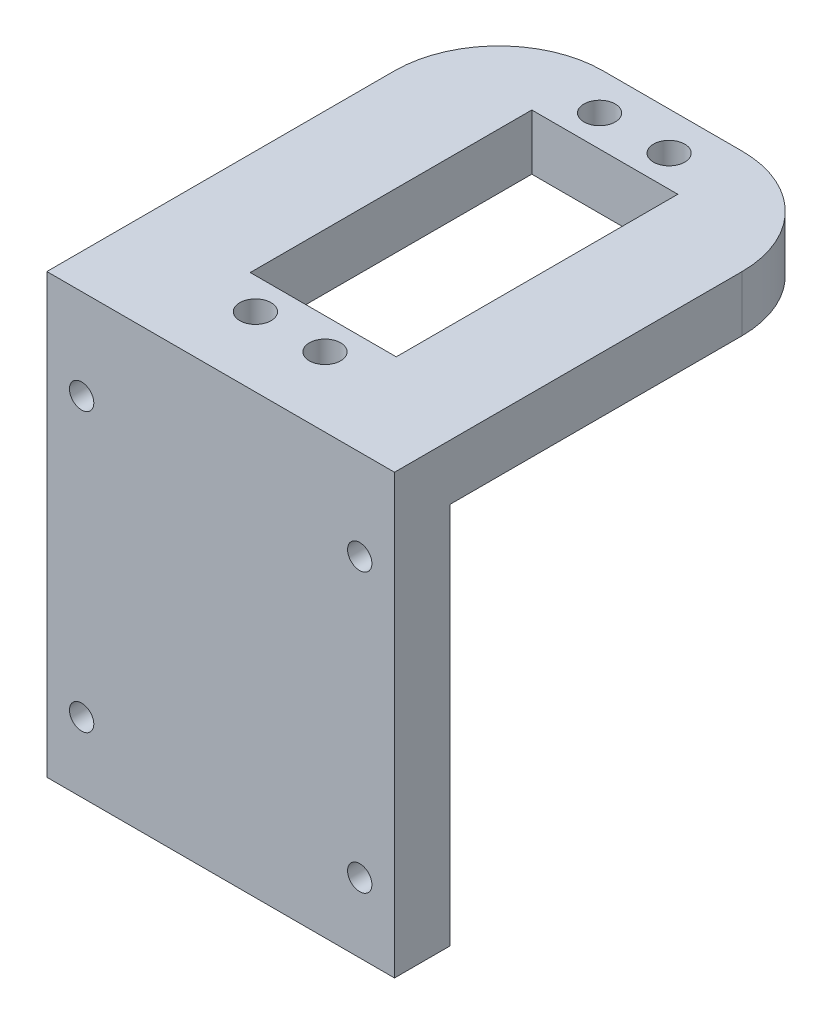
SolidWorks part; units mm, degrees
ref_plane "Front Plane" through (0, 0, 0) normal (0, 0, 1) x (1, 0, 0)
ref_plane "Top Plane" through (0, 0, 0) normal (0, 1, 0) x (1, 0, 0)
ref_plane "Right Plane" through (0, 0, 0) normal (1, 0, 0) x (0, 0, -1)
sketch "Sketch2" plane through (0, 0, 0) normal (0, 1, 0) x (1, 0, 0)
  line L1 (-25, 37.5) -> (25, 37.5)
  line L2 (-25, 37.5) -> (-25, -27.5)
  line L3 (-25, -27.5) -> (25, -27.5)
  line L4 (25, 37.5) -> (25, -27.5)
  dimension "D1" = 50
  dimension "D2" = 65
  dimension "D3" = 25
  dimension "D4" = 37.5
extrude "Boss-Extrude1" add sketch "Sketch2" along normal blind 8
sketch "Sketch4" plane through (0, 0, 0) normal (0, -1, 0) x (-1, 0, 0)
  line L0 (-25, -27.5) -> (-25, 37.5) construction
  line L1 (25, -27.5) -> (-25, -27.5)
  line L2 (25, -27.5) -> (25, -19.5)
  line L3 (25, -19.5) -> (-25, -19.5)
  line L4 (-25, -27.5) -> (-25, -19.5)
  dimension "D1" = 8
extrude "Boss-Extrude2" add sketch "Sketch4" along normal blind 55
sketch "Sketch6" plane through (0, 0, 19.5) normal (0, 0, -1) x (-1, 0, 0)
  line L0 (25, 0) -> (-25, 0) construction
  line L1 (-25, -55) -> (-25, 0) construction
  circle A0 centre (-20, -5) radius 1.75
  circle A1 centre (20, -5) radius 1.75
  circle A2 centre (-20, -45) radius 1.75
  circle A3 centre (20, -45) radius 1.75
  dimension "D1" = 3.5
  dimension "D2" = 3.5
  dimension "D3" = 3.5
  dimension "D4" = 3.5
  dimension "D5" = 5
  dimension "D6" = 5
  dimension "D7" = 40
  dimension "D8" = 40
  dimension "D9" = 40
  dimension "D10" = 5
  dimension "D11" = 5
extrude "Cut-Extrude1" cut sketch "Sketch6" against normal blind 10
sketch "Sketch7" plane through (0, 0, 19.5) normal (0, 0, -1) x (-1, 0, 0)
  circle A0 centre (-20, -5) radius 3.5
  circle A1 centre (20, -5) radius 3.5
  circle A2 centre (20, -45) radius 3.5
  circle A3 centre (-20, -45) radius 3.5
  dimension "D1" = 7
  dimension "D2" = 7
  dimension "D3" = 7
  dimension "D4" = 7
extrude "Cut-Extrude2" cut sketch "Sketch7" against normal blind 3
sketch "Sketch9" plane through (0, 8, 0) normal (0, 1, 0) x (1, 0, 0)
  line L0 (-25, -27.5) -> (25, -27.5) construction
  line L1 (-10.25, 27.5) -> (10.75, 27.5)
  line L2 (-10.25, 27.5) -> (-10.25, -13)
  line L3 (-10.25, -13) -> (10.75, -13)
  line L4 (10.75, 27.5) -> (10.75, -13)
  dimension "D1" = 21
  dimension "D2" = 40.5
  dimension "D3" = 10.25
  dimension "D4" = 55
extrude "Cut-Extrude3" cut sketch "Sketch9" against normal blind 10
sketch "Sketch10" plane through (0, 8, 0) normal (0, 1, 0) x (1, 0, 0)
  line L0 (10.75, 27.5) -> (-10.25, 27.5) construction
  circle A0 centre (-5, 32) radius 2.25
  circle A1 centre (5, 32) radius 2.25
  circle A2 centre (-5, -17.5) radius 2.25
  circle A3 centre (5, -17.5) radius 2.25
  dimension "D1" = 4.5
  dimension "D2" = 4.5
  dimension "D3" = 4.5
  dimension "D4" = 4.5
  dimension "D5" = 5
  dimension "D6" = 5
  dimension "D7" = 5
  dimension "D8" = 5
  dimension "D9" = 49.5
  dimension "D10" = 49.5
  dimension "D11" = 4.5
  dimension "D12" = 4.5
extrude "Cut-Extrude4" cut sketch "Sketch10" against normal blind 10
fillet "Fillet1" radius 15 1 edges at (25, 4, -37.5)
fillet "Fillet2" radius 15 1 edges at (-25, 4, -37.5)
